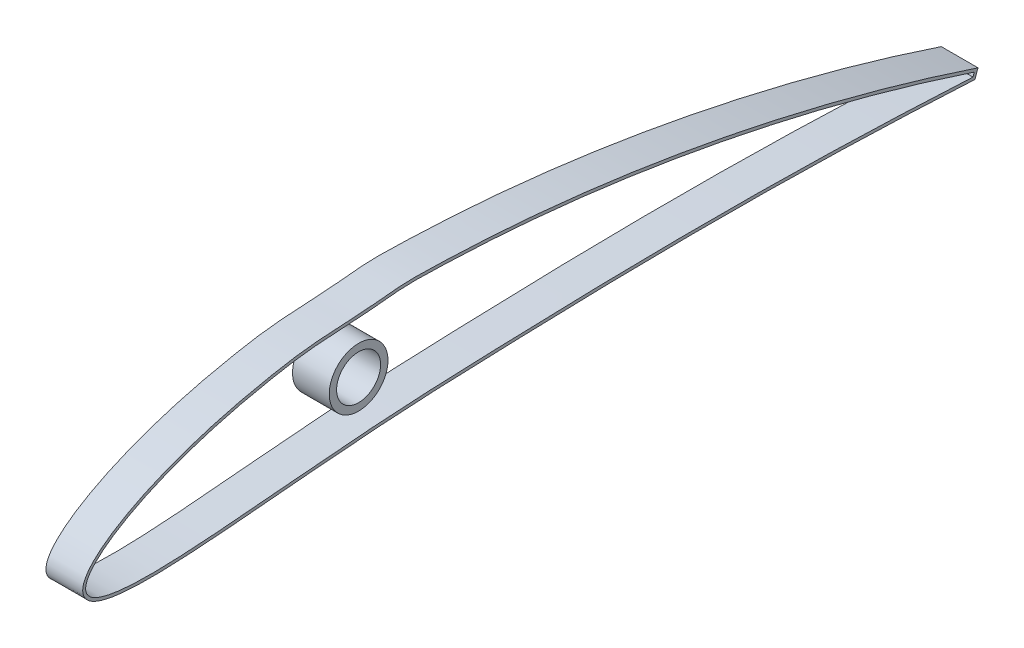
SolidWorks part; units mm, degrees
material "Özel Plastik"
ref_plane "Ön Düzlem" through (0, 0, 0) normal (0, 0, 1) x (1, 0, 0)
ref_plane "Üst Düzlem" through (0, 0, 0) normal (0, 1, 0) x (1, 0, 0)
ref_plane "Sağ Düzlem" through (0, 0, 0) normal (1, 0, 0) x (0, 0, -1)
curve "Eğri4"
  spline degree 3 poles (80, 0.31, -175.0625) (80, 0.3867, -174.84) (80, 0.6921, -173.9535) (80, 1.3769, -171.969) (80, 2.4819, -168.6784) (80, 3.9862, -164.1162) (80, 5.8281, -158.3215) (80, 7.9502, -151.3484) (80, 10.286, -143.2653) (80, 12.7621, -134.1499) (80, 15.3036, -124.0941) (80, 17.8302, -113.1988) (80, 20.2786, -101.5808) (80, 22.5695, -89.3612) (80, 24.6348, -76.6718) (80, 26.4243, -63.6518) (80, 27.867, -50.4485) (80, 28.9684, -37.1998) (80, 29.5516, -23.9789) (80, 29.9928, -12.8789) (80, 28.4163, -0.2259) (80, 28.3027, 11.9981) (80, 25.8795, 25.3048) (80, 23.5489, 35.7504) (80, 20.7792, 45.1453) (80, 17.7632, 53.3851) (80, 14.6071, 60.38) (80, 11.4359, 66.0639) (80, 8.3611, 70.4115) (80, 5.4496, 73.3996) (80, 2.6922, 75.1196) (80, -0.0831, 75.2755) (80, -2.3064, 73.6304) (80, -3.6987, 70.7464) (80, -4.6128, 66.7813) (80, -5.0919, 61.6729) (80, -5.1878, 55.472) (80, -4.9408, 48.2381) (80, -4.4119, 40.0526) (80, -3.6635, 30.9995) (80, -2.7813, 21.1668) (80, -1.8406, 10.6432) (80, -0.923, -0.4802) (80, -0.1139, -12.111) (80, 0.4958, -24.2454) (80, 0.9265, -36.7753) (80, 1.3705, -49.5696) (80, 1.7251, -62.4055) (80, 1.982, -75.14) (80, 2.126, -87.6371) (80, 2.1517, -99.7593) (80, 2.0666, -111.3714) (80, 1.8899, -122.3426) (80, 1.6272, -132.5463) (80, 1.3242, -141.8629) (80, 0.9858, -150.186) (80, 0.6635, -157.3993) (80, 0.3216, -163.4642) (80, 0.156, -168.1691) (80, -0.2646, -171.7924) (80, -0.0036, -173.588) (80, -0.512, -174.97) (80, -0.1212, -174.9929) (80, 0, -175) knots 0 0 0 0 0.001372 0.005465 0.012235 0.021602 0.033462 0.047672 0.064082 0.082498 0.102721 0.124529 0.147678 0.171915 0.196982 0.222601 0.248501 0.27439 0.300046 0.325695 0.338903 0.374269 0.396701 0.417567 0.436644 0.453735 0.468671 0.481321 0.491622 0.499607 0.505538 0.510177 0.514816 0.520693 0.528508 0.538458 0.550535 0.564636 0.580631 0.598338 0.617578 0.638168 0.659916 0.682627 0.706116 0.730723 0.755696 0.780728 0.805561 0.82993 0.853568 0.876211 0.897608 0.917518 0.935697 0.951942 0.966047 0.97784 0.987174 0.993931 0.998018 0.999386 1 1 1 1
sketch "Çizim2" plane through (0, 0, 0) normal (1, 0, 0) x (0, 0, -1)
  line L1 (174.6022, 0.0451) -> (174.7326, 0.4237) construction
  line L2 (175.0625, 0.31) -> (174.6932, 0.3093) construction
  line L3 (174.6022, 0.0451) -> (174.9807, -0.0853) construction
  line L4 (174.6932, 0.3093) -> (167.9731, 0.2974) construction
  line L5 (167.9731, 0.2974) -> (-74.9573, -0.1327) construction
  line L6 (168.7197, 2.4641) -> (167.9112, 0.1175)
  line L7 (167.6998, 1.9598) -> (167.3538, 0.9558)
  arc A0 (174.5025, -0.3426) -> (174.7326, 0.4237) centre (174.6022, 0.0451) ccw construction
  spline S0 degree 3 poles (-3452.5204, -12461.6619) (512.1978, -97.4511) (339.8366, -56.5562) (171.969, 1.3769) (168.6784, 2.4819) (164.1162, 3.9862) (158.3215, 5.8281) (151.3484, 7.9502) (143.2653, 10.286) (134.1499, 12.7621) (124.0941, 15.3036) (113.1988, 17.8302) (101.5808, 20.2786) (89.3612, 22.5695) (76.6718, 24.6348) (63.6518, 26.4243) (50.4485, 27.867) (37.1998, 28.9684) (23.9789, 29.5516) (12.8789, 29.9928) (0.2259, 28.4163) (-11.9981, 28.3027) (-25.3048, 25.8795) (-35.7504, 23.5489) (-45.1453, 20.7792) (-53.3851, 17.7632) (-60.38, 14.6071) (-66.0639, 11.4359) (-70.4115, 8.3611) (-73.3996, 5.4496) (-75.1196, 2.6922) (-75.2755, -0.0831) (-73.6304, -2.3064) (-70.7464, -3.6987) (-66.7813, -4.6128) (-61.6729, -5.0919) (-55.472, -5.1878) (-48.2381, -4.9408) (-40.0526, -4.4119) (-30.9995, -3.6635) (-21.1668, -2.7813) (-10.6432, -1.8406) (0.4802, -0.923) (12.111, -0.1139) (24.2454, 0.4958) (36.7753, 0.9265) (49.5696, 1.3705) (62.4055, 1.7251) (75.14, 1.982) (87.6371, 2.126) (99.7593, 2.1517) (111.3714, 2.0666) (122.3426, 1.8899) (132.5463, 1.6272) (141.8629, 1.3242) (150.186, 0.9858) (157.3993, 0.6635) (163.4642, 0.3216) (168.1691, 0.156) (171.7924, -0.2646) (173.588, -0.0036) (183.0389, -3.4806) (38.863, 191.9066) (8074.8977, -10248.1675) knots -1.022752 -1.022752 -1.022752 -1.022752 0.001372 0.005465 0.012235 0.021602 0.033462 0.047672 0.064082 0.082498 0.102721 0.124529 0.147678 0.171915 0.196982 0.222601 0.248501 0.27439 0.300046 0.325695 0.338903 0.374269 0.396701 0.417567 0.436644 0.453735 0.468671 0.481321 0.491622 0.499607 0.505538 0.510177 0.514816 0.520693 0.528508 0.538458 0.550535 0.564636 0.580631 0.598338 0.617578 0.638168 0.659916 0.682627 0.706116 0.730723 0.755696 0.780728 0.805561 0.82993 0.853568 0.876211 0.897608 0.917518 0.935697 0.951942 0.966047 0.97784 0.987174 0.993931 0.998018 0.999386 1.035434 1.035434 1.035434 1.035434 only from (175.0625, 0.31) to (175, 0) construction
  spline S1 degree 3 poles (168.7197, 2.4641) (167.3214, 2.9293) (163.9889, 4.0266) (158.3215, 5.8281) (151.3484, 7.9502) (143.2653, 10.286) (134.1499, 12.7621) (124.0941, 15.3036) (113.1988, 17.8302) (101.5808, 20.2786) (89.3612, 22.5695) (76.6718, 24.6348) (63.6518, 26.4243) (50.4485, 27.867) (37.1998, 28.9684) (23.9789, 29.5516) (12.8789, 29.9928) (0.2259, 28.4163) (-11.9981, 28.3027) (-25.3048, 25.8795) (-35.7504, 23.5489) (-45.1453, 20.7792) (-53.3851, 17.7632) (-60.38, 14.6071) (-66.0639, 11.4359) (-70.4115, 8.3611) (-73.3996, 5.4496) (-75.1196, 2.6922) (-75.2755, -0.0831) (-73.6304, -2.3064) (-70.7464, -3.6987) (-66.7813, -4.6128) (-61.6729, -5.0919) (-55.472, -5.1878) (-48.2381, -4.9408) (-40.0526, -4.4119) (-30.9995, -3.6635) (-21.1668, -2.7813) (-10.6432, -1.8406) (0.4802, -0.923) (12.111, -0.1139) (24.2454, 0.4958) (36.7753, 0.9265) (49.5696, 1.3705) (62.4055, 1.7251) (75.14, 1.982) (87.6371, 2.126) (99.7593, 2.1517) (111.3714, 2.0666) (122.3426, 1.8899) (132.5463, 1.6272) (141.8629, 1.3242) (150.186, 0.9858) (157.3993, 0.6635) (163.2166, 0.3355) (166.5432, 0.2136) (167.9112, 0.1175) knots 0.013014 0.013014 0.013014 0.013014 0.021602 0.033462 0.047672 0.064082 0.082498 0.102721 0.124529 0.147678 0.171915 0.196982 0.222601 0.248501 0.27439 0.300046 0.325695 0.338903 0.374269 0.396701 0.417567 0.436644 0.453735 0.468671 0.481321 0.491622 0.499607 0.505538 0.510177 0.514816 0.520693 0.528508 0.538458 0.550535 0.564636 0.580631 0.598338 0.617578 0.638168 0.659916 0.682627 0.706116 0.730723 0.755696 0.780728 0.805561 0.82993 0.853568 0.876211 0.897608 0.917518 0.935697 0.951942 0.966047 0.97784 0.985735 0.985735 0.985735 0.985735
  spline S2 degree 3 poles (174.7326, 0.4237) (174.6201, 0.4624) (173.8435, 0.73) (171.969, 1.3769) (170.0754, 2.0128) (168.8465, 2.422) (168.7197, 2.4641) knots 0.000678 0.000678 0.000678 0.000678 0.001372 0.005465 0.012235 0.013014 0.013014 0.013014 0.013014 construction
  spline S3 degree 3 poles (167.9112, 0.1175) (168.1604, 0.1) (169.5868, -0.0086) (171.7924, -0.2646) (173.4499, -0.0237) (174.4154, -0.3202) (174.5025, -0.3426) knots 0.985735 0.985735 0.985735 0.985735 0.987174 0.993931 0.998018 0.998446 0.998446 0.998446 0.998446 construction
  spline S4 degree 1 poles (167.6998, 1.9598) (167.3538, 0.9558) knots 0 0 1 1 construction
  spline S5 degree 3 poles (167.6998, 1.9598) (157.8415, 5.2265) (137.9344, 11.1979) (107.6223, 18.4739) (82.063, 23.1158) (64.0508, 25.5568) (53.7292, 26.6984) (45.9731, 27.4379) (38.21, 28.0457) (30.4451, 28.4679) (22.6426, 28.8093) (16.1581, 29.0299) (11.0275, 28.8602) (7.1867, 28.4817) (3.2793, 28.0655) (-1.9395, 27.7059) (-8.4387, 27.4034) (-16.1309, 26.7104) (-23.7748, 25.3332) (-31.3945, 23.7255) (-38.9138, 21.8166) (-46.3298, 19.5079) (-53.5975, 16.8001) (-59.477, 14.1303) (-63.9978, 11.6735) (-67.2659, 9.6321) (-70.3241, 7.3392) (-72.5656, 5.122) (-73.7584, 3.3501) (-74.1832, 2.3001) (-74.3583, 1.4702) (-74.3567, 0.6524) (-74.1034, -0.2975) (-73.2332, -1.4311) (-71.7618, -2.3445) (-69.4207, -3.212) (-66.3276, -3.8364) (-62.4985, -4.2053) (-58.635, -4.3478) (-54.7591, -4.3401) (-49.5838, -4.1927) (-43.1094, -3.825) (-35.3426, -3.2285) (-27.5749, -2.5543) (-17.2161, -1.6222) (-4.258, -0.4799) (11.3197, 0.6703) (26.9284, 1.4095) (42.5213, 1.9281) (58.1235, 2.4287) (78.9323, 2.881) (99.7498, 3.0079) (120.5663, 2.7428) (136.1722, 2.3392) (147.8775, 1.8888) (155.6683, 1.5404) (159.5789, 1.3402) (162.829, 1.1653) (165.3904, 1.0588) (166.7023, 0.9958) (167.3538, 0.9558) knots 0.014586 0.014586 0.014586 0.014586 0.07521 0.135834 0.196457 0.226769 0.241925 0.257081 0.272237 0.287393 0.302549 0.317705 0.325283 0.332861 0.340439 0.348016 0.363172 0.378328 0.393484 0.40864 0.423796 0.438952 0.454108 0.469264 0.476842 0.48442 0.491998 0.499576 0.503365 0.505259 0.507154 0.509048 0.510943 0.514732 0.51852 0.522309 0.529887 0.537465 0.545043 0.552621 0.560199 0.575355 0.590511 0.605667 0.620823 0.651135 0.681447 0.711758 0.74207 0.772382 0.802694 0.863317 0.893629 0.923941 0.954253 0.961831 0.969409 0.976987 0.980776 0.984565 0.984565 0.984565 0.984565
  point P3 (-74.9573, -0.1327)
  point P4 (168.3154, 1.2908)
  dimension "D1" = 6.75
  dimension "D2" = 0.8
extrude "Yükseklik-Ekstrüzyon1" add sketch "Çizim2" along normal mid plane 10
sketch "Çizim3" plane through (0, 0, 0) normal (1, 0, 0) x (0, 0, -1)
  line L1 (0, -0.9842) -> (0, 28.6475) construction
  circle A0 centre (0, 13.8316) radius 6
  circle A1 centre (0, 13.8316) radius 8
  spline S0 degree 3 poles (168.7197, 2.4641) (167.3214, 2.9293) (163.9889, 4.0266) (158.3215, 5.8281) (151.3484, 7.9502) (143.2653, 10.286) (134.1499, 12.7621) (124.0941, 15.3036) (113.1988, 17.8302) (101.5808, 20.2786) (89.3612, 22.5695) (76.6718, 24.6348) (63.6518, 26.4243) (50.4485, 27.867) (37.1998, 28.9684) (23.9789, 29.5516) (12.8789, 29.9928) (0.2259, 28.4163) (-11.9981, 28.3027) (-25.3048, 25.8795) (-35.7504, 23.5489) (-45.1453, 20.7792) (-53.3851, 17.7632) (-60.38, 14.6071) (-66.0639, 11.4359) (-70.4115, 8.3611) (-73.3996, 5.4496) (-75.1196, 2.6922) (-75.2755, -0.0831) (-73.6304, -2.3064) (-70.7464, -3.6987) (-66.7813, -4.6128) (-61.6729, -5.0919) (-55.472, -5.1878) (-48.2381, -4.9408) (-40.0526, -4.4119) (-30.9995, -3.6635) (-21.1668, -2.7813) (-10.6432, -1.8406) (0.4802, -0.923) (12.111, -0.1139) (24.2454, 0.4958) (36.7753, 0.9265) (49.5696, 1.3705) (62.4055, 1.7251) (75.14, 1.982) (87.6371, 2.126) (99.7593, 2.1517) (111.3714, 2.0666) (122.3426, 1.8899) (132.5463, 1.6272) (141.8629, 1.3242) (150.186, 0.9858) (157.3993, 0.6635) (163.2166, 0.3355) (166.5432, 0.2136) (167.9112, 0.1175) knots 0.013014 0.013014 0.013014 0.013014 0.021602 0.033462 0.047672 0.064082 0.082498 0.102721 0.124529 0.147678 0.171915 0.196982 0.222601 0.248501 0.27439 0.300046 0.325695 0.338903 0.374269 0.396701 0.417567 0.436644 0.453735 0.468671 0.481321 0.491622 0.499607 0.505538 0.510177 0.514816 0.520693 0.528508 0.538458 0.550535 0.564636 0.580631 0.598338 0.617578 0.638168 0.659916 0.682627 0.706116 0.730723 0.755696 0.780728 0.805561 0.82993 0.853568 0.876211 0.897608 0.917518 0.935697 0.951942 0.966047 0.97784 0.985735 0.985735 0.985735 0.985735 construction
  dimension "D1" = 12
  dimension "D2" = 16
extrude "Yükseklik-Ekstrüzyon2" add sketch "Çizim3" along normal mid plane 10 separate body
